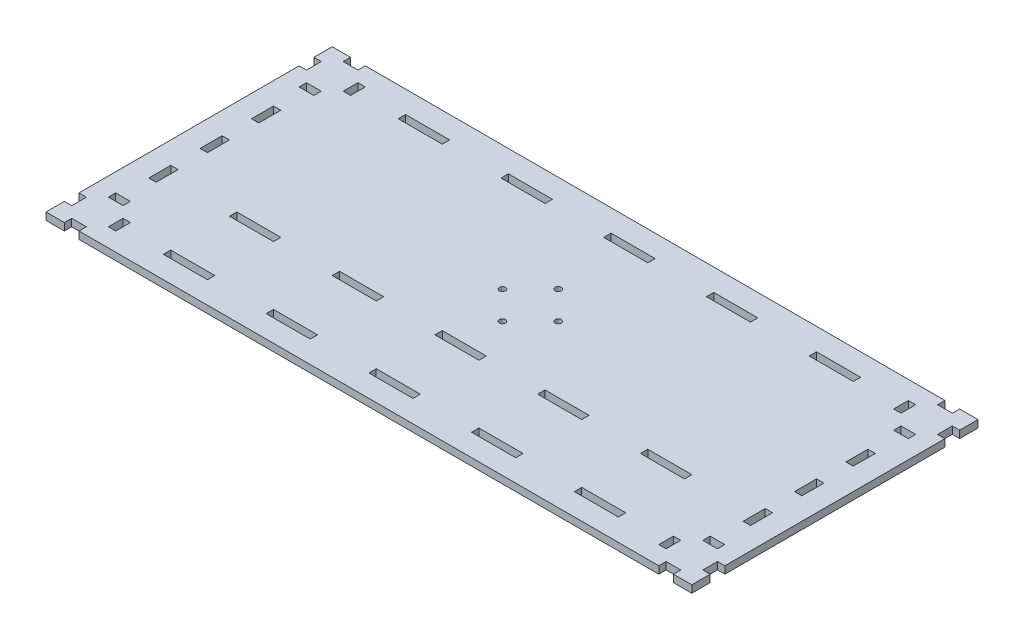
SolidWorks part; units mm, degrees
ref_plane "Front Plane" through (0, 0, 0) normal (0, 0, 1) x (1, 0, 0)
ref_plane "Top Plane" through (0, 0, 0) normal (0, 1, 0) x (1, 0, 0)
ref_plane "Right Plane" through (0, 0, 0) normal (1, 0, 0) x (0, 0, -1)
sketch "Sketch2" plane through (0, -435, 0) normal (0, 1, 0) x (1, 0, 0)
  line L0 (-225, 6.1) -> (-225, -42.7468) construction
  line L1 (-221.1, 10) -> (-199.9999, 10) construction
  line L2 (-445, -2.5) -> (-383.8936, -2.5) construction
  line L3 (-100, -80) -> (-100, -85)
  line L4 (-70, -80) -> (-100, -80)
  line L5 (-70, -85) -> (-70, -80)
  line L6 (-100, -85) -> (-70, -85)
  line L7 (-170, -80) -> (-170, -85)
  line L8 (-17.5, 65) -> (-27.5, 65)
  line L9 (-27.5, 65) -> (-27.5, 60)
  line L10 (-27.5, 60) -> (-17.5, 60)
  line L11 (-17.5, 60) -> (-17.5, 65)
  line L12 (-140, -80) -> (-170, -80)
  line L13 (-140, -85) -> (-140, -80)
  line L14 (-170, -85) -> (-140, -85)
  line L15 (-240, -80) -> (-240, -85)
  line L16 (-35.0003, 82.5) -> (-40, 82.5)
  line L17 (-40, 82.5) -> (-40, 72.5)
  line L18 (-40, 72.5) -> (-35.0003, 72.5)
  line L19 (-35.0003, 72.5) -> (-35.0003, 82.5)
  line L20 (-210, -80) -> (-240, -80)
  line L21 (-210, -85) -> (-210, -80)
  line L22 (-430, -45) -> (-430, -30)
  line L23 (-430, -30) -> (-425, -30)
  line L24 (-422.5, 60) -> (-422.5, 65)
  line L25 (-432.5, 60) -> (-422.5, 60)
  line L26 (-432.5, 65) -> (-432.5, 60)
  line L27 (-422.5, 65) -> (-432.5, 65)
  line L28 (-425, -30) -> (-425, -45)
  line L29 (-425, -45) -> (-430, -45)
  line L30 (-430, -10) -> (-430, 5)
  line L31 (-430, 5) -> (-425, 5)
  line L32 (-414.9997, 82.5) -> (-414.9997, 72.5)
  line L33 (-414.9997, 72.5) -> (-410, 72.5)
  line L34 (-410, 72.5) -> (-410, 82.5)
  line L35 (-410, 82.5) -> (-414.9997, 82.5)
  line L36 (-425, 5) -> (-425, -10)
  line L37 (-425, -10) -> (-430, -10)
  line L38 (-430, 25) -> (-430, 40)
  line L39 (-430, 40) -> (-425, 40)
  line L40 (-414.9997, -87.5) -> (-410, -87.5)
  line L41 (-410, -87.5) -> (-410, -77.5)
  line L42 (-410, -77.5) -> (-414.9997, -77.5)
  line L43 (-414.9997, -77.5) -> (-414.9997, -87.5)
  line L44 (-425, 40) -> (-425, 25)
  line L45 (-425, 25) -> (-430, 25)
  line L46 (-25, 25) -> (-20, 25)
  line L47 (-25, 40) -> (-25, 25)
  line L48 (-422.5, -70) -> (-422.5, -65)
  line L49 (-432.5, -70) -> (-422.5, -70)
  line L50 (-432.5, -65) -> (-432.5, -70)
  line L51 (-422.5, -65) -> (-432.5, -65)
  line L52 (-20, 40) -> (-25, 40)
  line L53 (-20, 25) -> (-20, 40)
  line L54 (-25, -10) -> (-20, -10)
  line L55 (-25, 5) -> (-25, -10)
  line L56 (-27.5, -65) -> (-27.5, -70)
  line L57 (-17.5, -65) -> (-27.5, -65)
  line L58 (-17.5, -70) -> (-17.5, -65)
  line L59 (-27.5, -70) -> (-17.5, -70)
  line L60 (-20, 5) -> (-25, 5)
  line L61 (-20, -10) -> (-20, 5)
  line L62 (-25, -45) -> (-20, -45)
  line L63 (-25, -30) -> (-25, -45)
  line L64 (-35.0003, -77.5) -> (-40, -77.5)
  line L65 (-35.0003, -87.5) -> (-35.0003, -77.5)
  line L66 (-40, -87.5) -> (-35.0003, -87.5)
  line L67 (-40, -77.5) -> (-40, -87.5)
  line L68 (-20, -30) -> (-25, -30)
  line L69 (-20, -45) -> (-20, -30)
  line L70 (-240, -85) -> (-210, -85)
  line L71 (-310, -80) -> (-310, -85)
  line L72 (-280, -80) -> (-310, -80)
  line L73 (-280, -85) -> (-280, -80)
  line L74 (-310, -85) -> (-280, -85)
  line L75 (-380, -80) -> (-380, -85)
  line L76 (-350, -80) -> (-380, -80)
  line L77 (-350, -85) -> (-350, -80)
  line L78 (-380, -85) -> (-350, -85)
  line L90 (-380, 80) -> (-350, 80)
  line L91 (-350, 80) -> (-350, 75)
  line L92 (-350, 75) -> (-380, 75)
  line L93 (-380, 75) -> (-380, 80)
  line L94 (-310, 80) -> (-280, 80)
  line L95 (-280, 80) -> (-280, 75)
  line L96 (-280, 75) -> (-310, 75)
  line L97 (-310, 75) -> (-310, 80)
  line L98 (-240, 80) -> (-210, 80)
  line L99 (-210, 80) -> (-210, 75)
  line L100 (-210, 75) -> (-240, 75)
  line L101 (-240, 75) -> (-240, 80)
  line L102 (-170, 80) -> (-140, 80)
  line L103 (-140, 80) -> (-140, 75)
  line L104 (-140, 75) -> (-170, 75)
  line L105 (-170, 75) -> (-170, 80)
  line L106 (-100, 80) -> (-70, 80)
  line L107 (-70, 80) -> (-70, 75)
  line L108 (-70, 75) -> (-100, 75)
  line L109 (-100, 75) -> (-100, 80)
  line L119 (-380, -35) -> (-350, -35)
  line L120 (-350, -35) -> (-350, -40)
  line L121 (-350, -40) -> (-380, -40)
  line L122 (-380, -40) -> (-380, -35)
  line L123 (-310, -35) -> (-280, -35)
  line L124 (-280, -35) -> (-280, -40)
  line L125 (-280, -40) -> (-310, -40)
  line L126 (-310, -40) -> (-310, -35)
  line L127 (-240, -35) -> (-210, -35)
  line L128 (-210, -35) -> (-210, -40)
  line L129 (-210, -40) -> (-240, -40)
  line L130 (-240, -40) -> (-240, -35)
  line L131 (-170, -35) -> (-140, -35)
  line L132 (-140, -35) -> (-140, -40)
  line L133 (-140, -40) -> (-170, -40)
  line L134 (-170, -40) -> (-170, -35)
  line L135 (-100, -35) -> (-70, -35)
  line L136 (-17.5, -95) -> (-17.5, -100)
  line L137 (-27.5, -95) -> (-17.5, -95)
  line L138 (-27.5, -100) -> (-27.5, -95)
  line L139 (-422.5, -100) -> (-27.5, -100)
  line L140 (-422.5, -95) -> (-422.5, -100)
  line L141 (-432.5, -95) -> (-422.5, -95)
  line L142 (-432.5, -100) -> (-432.5, -95)
  line L143 (-445, -100) -> (-432.5, -100)
  line L144 (-445, -87.5) -> (-445, -100)
  line L145 (-440, -87.5) -> (-445, -87.5)
  line L146 (-440, -77.5) -> (-440, -87.5)
  line L147 (-445, -77.5) -> (-440, -77.5)
  line L148 (-445, 72.5) -> (-445, -77.5)
  line L149 (-440, 72.5) -> (-445, 72.5)
  line L150 (-440, 82.5) -> (-440, 72.5)
  line L151 (-445, 82.5) -> (-440, 82.5)
  line L152 (-445, 95) -> (-445, 82.5)
  line L153 (-432.5, 95) -> (-445, 95)
  line L154 (-432.5, 90) -> (-432.5, 95)
  line L155 (-422.5, 90) -> (-432.5, 90)
  line L156 (-422.5, 95) -> (-422.5, 90)
  line L157 (-27.5, 95) -> (-422.5, 95)
  line L158 (-27.5, 90) -> (-27.5, 95)
  line L159 (-17.5, 90) -> (-27.5, 90)
  line L160 (-17.5, 95) -> (-17.5, 90)
  line L161 (-5, 95) -> (-17.5, 95)
  line L162 (-5, 82.5) -> (-5, 95)
  line L163 (-10, 82.5) -> (-5, 82.5)
  line L164 (-10, 72.5) -> (-10, 82.5)
  line L165 (-5, 72.5) -> (-10, 72.5)
  line L166 (-5, -77.5) -> (-5, 72.5)
  line L167 (-10, -77.5) -> (-5, -77.5)
  line L168 (-10, -87.5) -> (-10, -77.5)
  line L169 (-5, -87.5) -> (-10, -87.5)
  line L170 (-5, -100) -> (-5, -87.5)
  line L171 (-17.5, -100) -> (-5, -100)
  line L172 (-70, -35) -> (-70, -40)
  line L173 (-70, -40) -> (-100, -40)
  line L174 (-100, -40) -> (-100, -35)
  circle A0 centre (-225, -9) radius 2.1
  circle A1 centre (-225, 29) radius 2.1
  circle A3 centre (-206, 10) radius 2.1
  circle A5 centre (-244, 10) radius 2.1
  dimension "D1" = 4.2
  dimension "D2" = 19
  dimension "D3" = 4.2
  dimension "D4" = 19
extrude "Boss-Extrude1" add sketch "Sketch2" along normal blind 5
